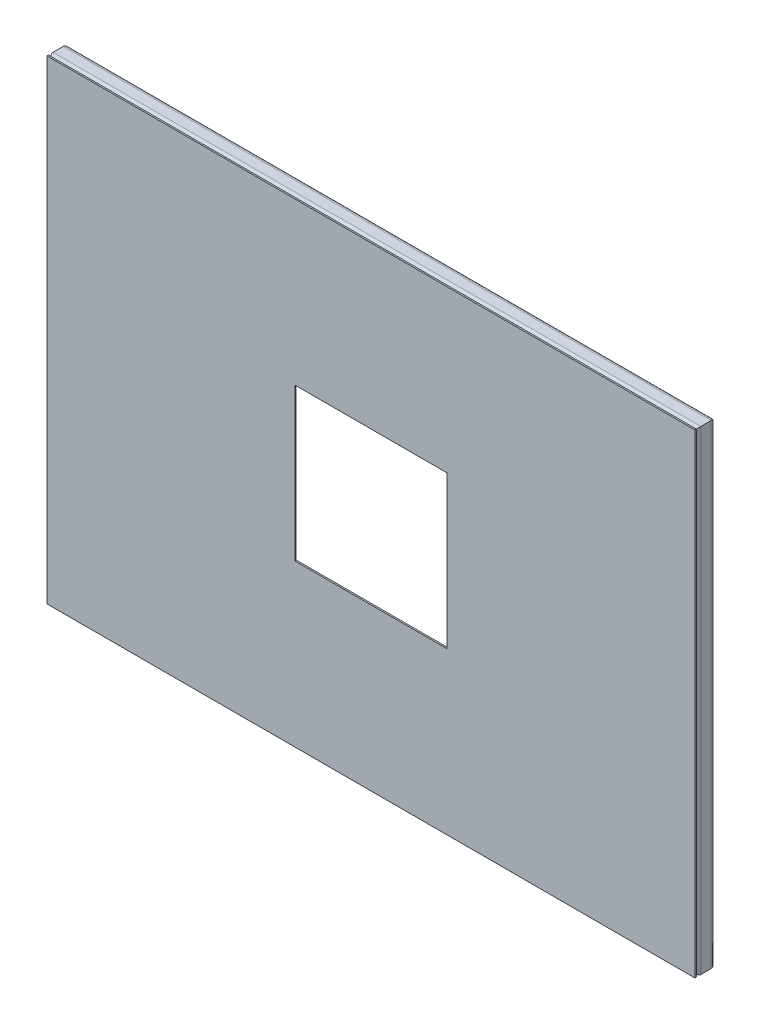
SolidWorks part; units mm, degrees
ref_plane "Alzado" through (0, 0, 0) normal (0, 0, 1) x (1, 0, 0)
ref_plane "Planta" through (0, 0, 0) normal (0, 1, 0) x (1, 0, 0)
ref_plane "Vista lateral" through (0, 0, 0) normal (1, 0, 0) x (0, 0, -1)
sketch "Croquis1" plane through (0, 0, 0) normal (0, 0, 1) x (1, 0, 0)
  line L1 (-400, 286.25) -> (400, 286.25)
  line L2 (-400, 286.25) -> (-400, -286.25)
  line L3 (-400, -286.25) -> (400, -286.25)
  line L4 (400, 286.25) -> (400, -286.25)
  line L5 (-400, 286.25) -> (400, -286.25) construction
  line L6 (-400, -286.25) -> (400, 286.25) construction
  point P0 (0, 0)
  dimension "D1" = 800
  dimension "D2" = 572.5
other "Tubo cuadrado 2 X 2 X 0.25(1)"
ref_plane "Plano1" through (-412.7, 286.25, -6.7) normal (0, -1, 0) x (1, 0, 0)
sketch "Sketch1" plane through (-412.7, 286.25, -6.7) normal (0, -1, 0) x (1, 0, 0)
  line L0 (-6.7, -9.7) -> (6.7, -9.7)
  line L1 (-9.7, -6.7) -> (-9.7, 6.7)
  line L2 (6.7, 9.7) -> (-6.7, 9.7)
  line L3 (9.7, 6.7) -> (9.7, -6.7)
  line L4 (-6.7, -12.7) -> (6.7, -12.7)
  line L5 (-12.7, -6.7) -> (-12.7, 6.7)
  line L6 (6.7, 12.7) -> (-6.7, 12.7)
  line L7 (12.7, 6.7) -> (12.7, -6.7)
  line L8 (0, 0) -> (9.7, 0) construction
  line L9 (0, 0) -> (0, 9.7) construction
  arc A0 (12.7, 6.7) -> (6.7, 12.7) centre (6.7, 6.7) ccw
  arc A1 (6.7, -12.7) -> (12.7, -6.7) centre (6.7, -6.7) ccw
  arc A2 (-12.7, -6.7) -> (-6.7, -12.7) centre (-6.7, -6.7) ccw
  arc A3 (-6.7, 12.7) -> (-12.7, 6.7) centre (-6.7, 6.7) ccw
  arc A4 (-6.7, 9.7) -> (-9.7, 6.7) centre (-6.7, 6.7) ccw
  arc A5 (9.7, 6.7) -> (6.7, 9.7) centre (6.7, 6.7) ccw
  arc A6 (6.7, -9.7) -> (9.7, -6.7) centre (6.7, -6.7) ccw
  arc A7 (-9.7, -6.7) -> (-6.7, -9.7) centre (-6.7, -6.7) ccw
  point P3 (0, 12.7)
  point P4 (12.7, 0)
  point P5 (0, -12.7)
  point P6 (-12.7, 0)
  point P7 (-12.7, 12.7)
  point P8 (-12.7, -12.7)
  point P33 (0, 0)
  point P35 (12.7, -12.7)
  point P36 (12.7, 12.7)
  point P37 (0, 0)
  dimension "D1" = 6
  dimension "Thickness" = 3
  dimension "V_leg" = 25.4
sketch "Croquis3" plane through (0, 0, 6) normal (0, 0, 1) x (1, 0, 0)
  line L1 (-425.4, -311.65) -> (425.4, -311.65)
  line L2 (-425.4, -311.65) -> (-425.4, 311.65)
  line L3 (-425.4, 311.65) -> (425.4, 311.65)
  line L4 (425.4, -311.65) -> (425.4, 311.65)
  line L5 (-425.4, -311.65) -> (425.4, 311.65) construction
  line L6 (-425.4, 311.65) -> (425.4, -311.65) construction
  point P0 (0, 0)
extrude "Saliente-Extruir1" add sketch "Croquis3" along normal blind 1.9 separate body
sketch "Croquis4" plane through (0, 0, 7.9) normal (0, 0, 1) x (1, 0, 0)
  line L2 (-100, -100) -> (100, -100)
  line L3 (-100, -100) -> (-100, 100)
  line L4 (-100, 100) -> (100, 100)
  line L5 (100, -100) -> (100, 100)
  line L6 (-100, -100) -> (100, 100) construction
  line L7 (-100, 100) -> (100, -100) construction
  point P0 (0, 0)
  point P1 (0, 0)
  dimension "D1" = 200
  dimension "D2" = 200
extrude "Cortar-Extruir2" cut sketch "Croquis4" against normal blind 10
